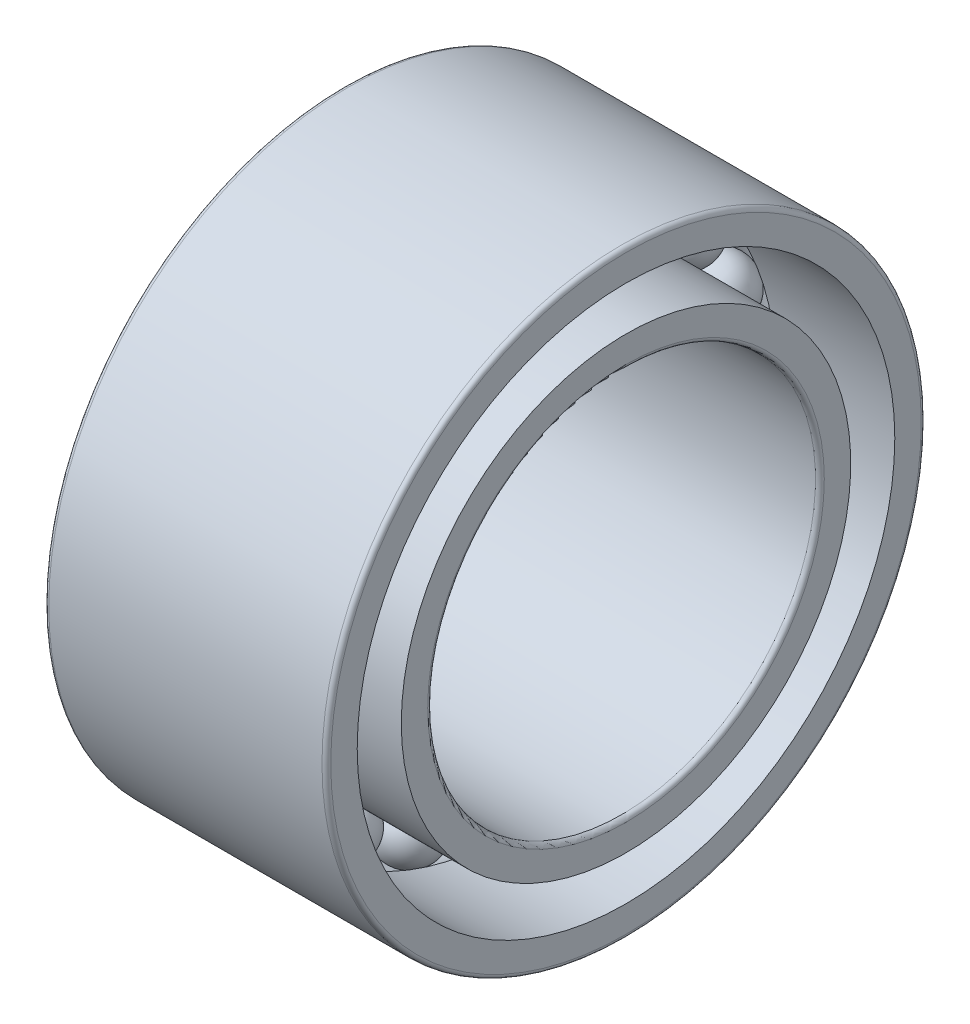
SolidWorks part; units mm, degrees
other "outer ring"
other "inner ring"
other "ball"
ref_plane "Front Plane" through (0, 0, 0) normal (0, 0, 1) x (1, 0, 0)
ref_plane "Top Plane" through (0, 0, 0) normal (0, 1, 0) x (1, 0, 0)
ref_plane "Right Plane" through (0, 0, 0) normal (1, 0, 0) x (0, 0, -1)
sketch "Sketch2" plane through (0, 0, 0) normal (0, 0, 1) x (1, 0, 0)
  line L0 (0, 0) -> (0, 17) construction
  line L1 (0, 0) -> (8, 0) construction
  line L2 (-7.75, 17) -> (7.75, 17)
  line L3 (-8, 16.75) -> (-8, 15.25)
  line L4 (-8, 15.25) -> (-1.2247, 15.25)
  line L5 (1.2247, 15.25) -> (8, 15.25)
  line L6 (8, 15.25) -> (8, 16.75)
  line L7 (-1.75, 14) -> (1.75, 14) construction
  line L8 (8, 12.75) -> (8, 11.25)
  line L9 (1.2247, 12.75) -> (8, 12.75)
  line L10 (-8, 12.75) -> (-1.2247, 12.75)
  line L11 (-8, 11.25) -> (-8, 12.75)
  line L12 (-7.75, 11) -> (7.75, 11)
  circle A0 centre (0, 14) radius 1.75 construction
  arc A1 (-1.2247, 15.25) -> (1.2247, 15.25) centre (0, 14) cw
  arc A2 (7.75, 17) -> (8, 16.75) centre (7.75, 16.75) cw
  arc A3 (-7.75, 17) -> (-8, 16.75) centre (-7.75, 16.75) ccw
  arc A4 (-7.75, 11) -> (-8, 11.25) centre (-7.75, 11.25) cw
  arc A5 (7.75, 11) -> (8, 11.25) centre (7.75, 11.25) ccw
  arc A6 (-1.2247, 12.75) -> (1.2247, 12.75) centre (0, 14) ccw
  point P9 (0, 17)
  point P16 (8, 17)
  point P19 (-8, 17)
  point P32 (-8, 11)
  point P33 (8, 11)
  point P34 (0, 11)
  point P35 (0, 0)
  point P36 (0, 0)
  dimension "D4" = 3.5
  dimension "D7" = 0.25
  dimension "D1" = 8
  dimension "D2" = 17
  dimension "D3" = 14
  dimension "D6" = 1.25
revolve "Revolve1" add sketch "Sketch2" angle 360 about L1
sketch "Sketch3" plane through (0, 0, 0) normal (0, 0, 1) x (1, 0, 0)
  line L1 (-1.75, 14) -> (1.75, 14)
  arc A1 (1.75, 14) -> (-1.75, 14) centre (0, 14) cw
revolve "Revolve2" add sketch "Sketch3" angle 360 about L7
pattern_circular "CirPattern1" count 20 over 360 about axis through (0, 0, 0) along (1, 0, 0) of bodies 103
